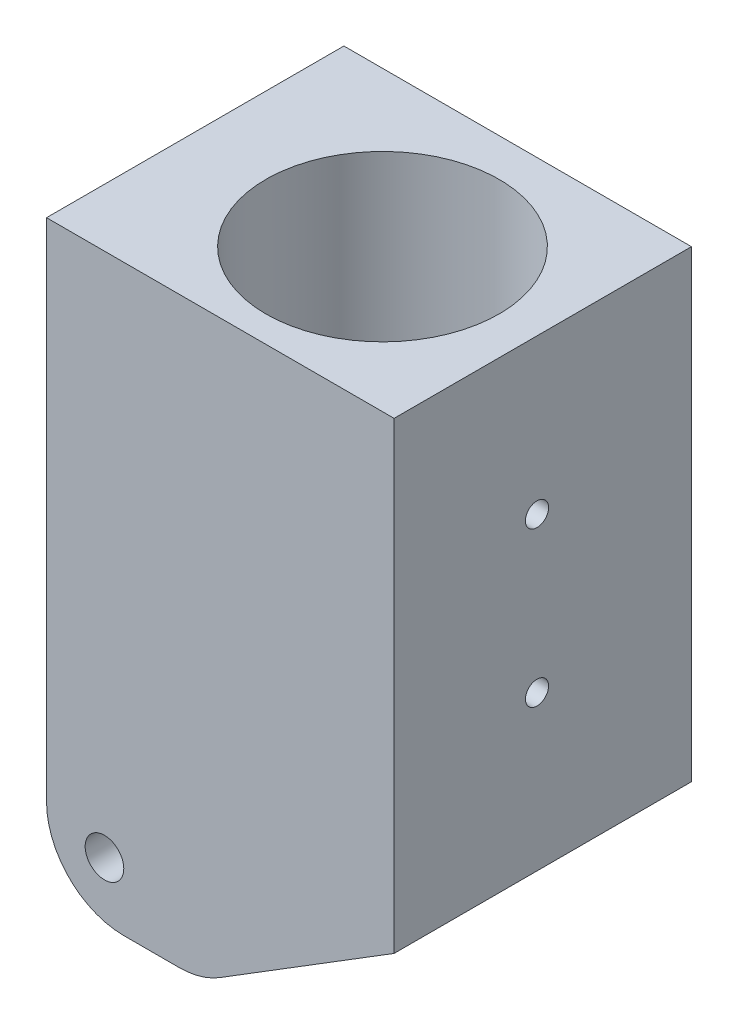
SolidWorks part; units mm, degrees
ref_plane "前基準面" through (0, 0, 0) normal (0, 0, 1) x (1, 0, 0)
ref_plane "上基準面" through (0, 0, 0) normal (0, 1, 0) x (1, 0, 0)
ref_plane "右基準面" through (0, 0, 0) normal (1, 0, 0) x (0, 0, -1)
sketch "草圖1" plane through (0, 0, 0) normal (0, 1, 0) x (1, 0, 0)
  line L1 (-25, 20) -> (20, 20)
  line L2 (-25, 20) -> (-25, -18.5)
  line L3 (-25, -18.5) -> (20, -18.5)
  line L4 (20, 20) -> (20, -18.5)
  dimension "D1" = 20
  dimension "D2" = 38.5
  dimension "D3" = 45
  dimension "D4" = 20
extrude "填料-伸長1" add sketch "草圖1" along normal blind 60
sketch "草圖2" plane through (0, 60, 0) normal (0, 1, 0) x (1, 0, 0)
  circle A0 centre (0, 0) radius 15.1
  dimension "D1" = 30.2
extrude "除料-伸長1" cut sketch "草圖2" against normal blind 50
sketch "草圖3" plane through (0, 0, 18.5) normal (0, 0, 1) x (1, 0, 0)
  line L2 (-25, 0) -> (-25, -15.5)
  line L3 (-25, -15.5) -> (-5, -15.5)
  line L4 (-5, -15.5) -> (20, 0)
  line L5 (20, 0) -> (-25, 0)
  circle A1 centre (-17.5, -8) radius 2.5
  dimension "D1" = 5
  dimension "D4" = 7.5
  dimension "D2" = 20
  dimension "D3" = 15.5
  dimension "D5" = 8
extrude "填料-伸長2" add sketch "草圖3" against normal blind 5
sketch "草圖4" plane through (20, 0, 0) normal (1, 0, 0) x (0, 0, -1)
  circle A0 centre (0, 20) radius 1.5
  dimension "D1" = 3
  dimension "D2" = 20
extrude "除料-伸長2" cut sketch "草圖4" against normal through all
pattern_linear "直線複製排列1" count 2 spacing 20 along (0, 1, 0) of "除料-伸長2"
fillet "圓角1" radius 10 2 edges at (-5, -15.5, 16) (-25, -15.5, 16)
